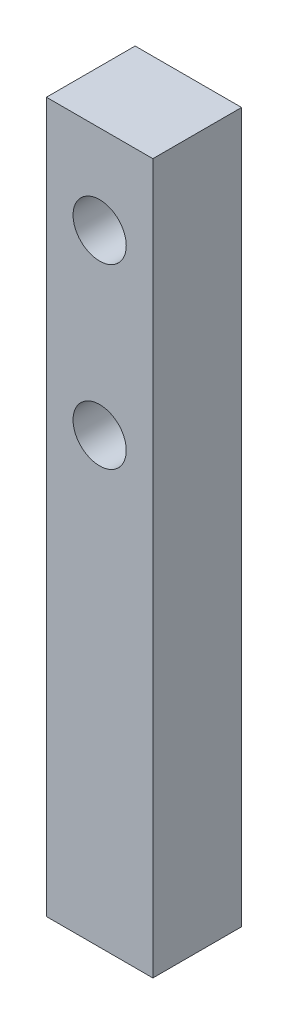
SolidWorks part; units mm, degrees
ref_plane "Front Plane" through (0, 0, 0) normal (0, 0, 1) x (1, 0, 0)
ref_plane "Top Plane" through (0, 0, 0) normal (0, 1, 0) x (1, 0, 0)
ref_plane "Right Plane" through (0, 0, 0) normal (1, 0, 0) x (0, 0, -1)
sketch "Sketch1" plane through (0, 0, 0) normal (0, 0, 1) x (1, 0, 0)
  line L0 (3.81, 0) -> (3.81, 50.8) construction
  line L1 (0, 0) -> (7.62, 0)
  line L2 (0, 0) -> (0, 50.8)
  line L3 (0, 50.8) -> (7.62, 50.8)
  line L4 (7.62, 0) -> (7.62, 50.8)
  circle A0 centre (3.81, 44.45) radius 1.905
  circle A1 centre (3.81, 31.75) radius 1.905
  dimension "D3" = 3.81
  dimension "D4" = 3.81
  dimension "D5" = 12.7
  dimension "D6" = 6.35
  dimension "D1" = 50.8
  dimension "D2" = 7.62
extrude "Boss-Extrude1" add sketch "Sketch1" along normal blind 6.35
